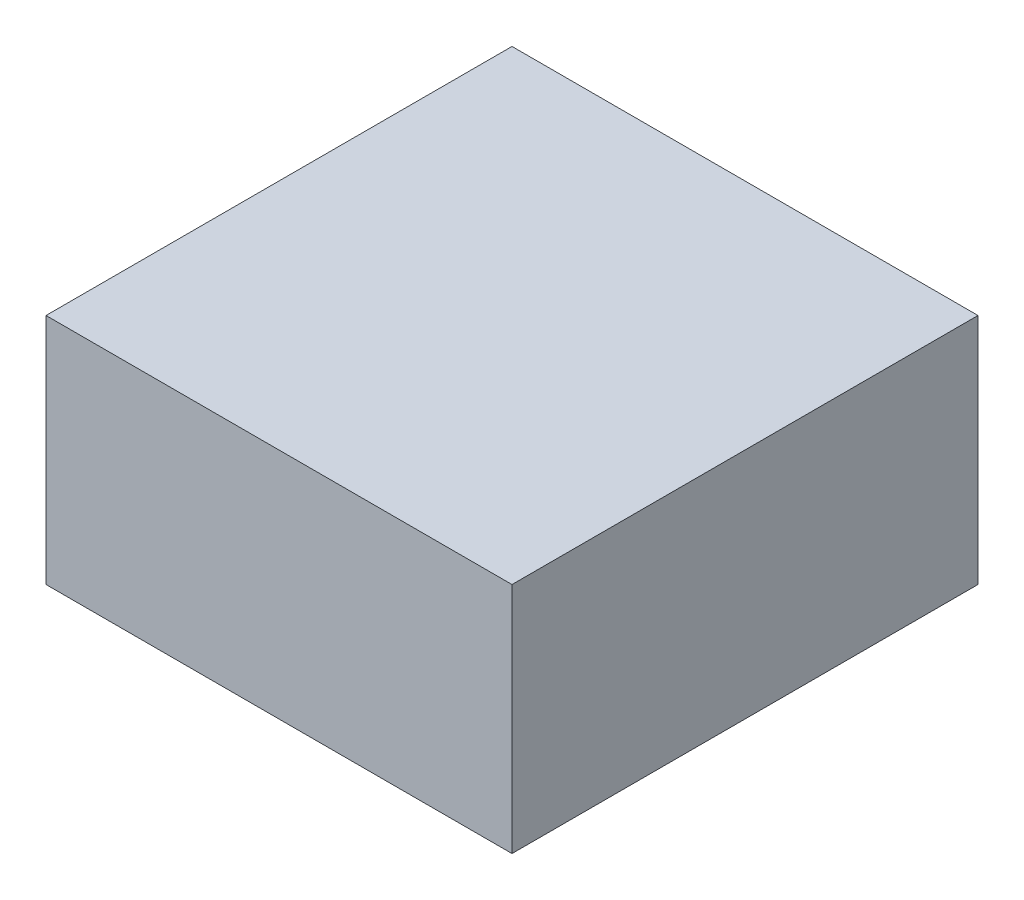
SolidWorks part; units mm, degrees
ref_plane "前视基准面" through (0, 0, 0) normal (0, 0, 1) x (1, 0, 0)
ref_plane "上视基准面" through (0, 0, 0) normal (0, 1, 0) x (1, 0, 0)
ref_plane "右视基准面" through (0, 0, 0) normal (1, 0, 0) x (0, 0, -1)
other "Configuration Table"
sketch "草图1" plane through (0, 0, 0) normal (0, 0, 1) x (1, 0, 0)
  line L1 (-28.5784, 10.0156) -> (-18.5784, 10.0156)
  line L2 (-28.5784, 10.0156) -> (-28.5784, 5.0156)
  line L3 (-28.5784, 5.0156) -> (-18.5784, 5.0156)
  line L4 (-18.5784, 10.0156) -> (-18.5784, 5.0156)
  line L5 (-28.5784, 10.0156) -> (-18.5784, 5.0156) construction
  line L6 (-28.5784, 5.0156) -> (-18.5784, 10.0156) construction
  point P0 (-23.5784, 7.5156)
  dimension "D1" = 5
  dimension "D2" = 10
extrude "凸台-拉伸1" add sketch "草图1" along normal blind 10
